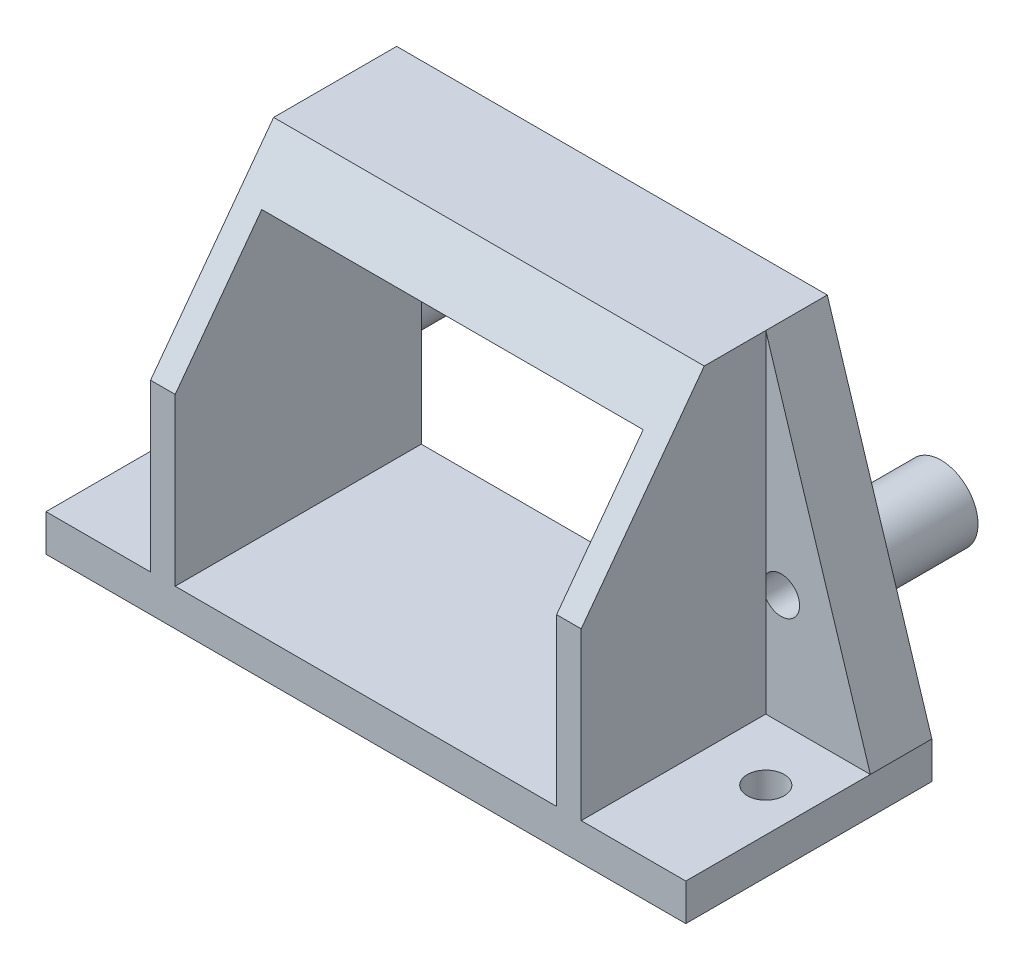
SolidWorks part; units mm, degrees
ref_plane "Front" through (0, 0, 0) normal (0, 0, 1) x (1, 0, 0)
ref_plane "Top" through (0, 0, 0) normal (0, 1, 0) x (1, 0, 0)
ref_plane "Right" through (0, 0, 0) normal (1, 0, 0) x (0, 0, -1)
sketch "草图1" plane through (0, 0, 0) normal (0, 0, 1) x (1, 0, 0)
  line L0 (-26, 0) -> (26, 0)
  line L1 (26, 0) -> (26, 3)
  line L2 (17.5, 30) -> (-17.5, 30)
  line L3 (-26, 3) -> (-26, 0)
  line L4 (-15.5, 3) -> (-15.5, 26)
  line L5 (-15.5, 26) -> (15.5, 26)
  line L6 (15.5, 26) -> (15.5, 3)
  line L7 (-15.5, 3) -> (15.5, 3)
  line L9 (17.5, 30) -> (26, 3)
  line L10 (-26, 3) -> (-17.5, 30)
extrude "凸台-拉伸1" add sketch "草图1" along normal blind 20
sketch "草图2" plane through (-15.5, 0, 0) normal (1, 0, 0) x (0, 0, -1)
  line L0 (-20, 16.5) -> (-10, 30)
  line L1 (-20, 3) -> (-20, 30) construction
  line L2 (-20, 30) -> (0, 30) construction
  line L3 (-10, 30) -> (-20, 30)
  line L4 (-20, 30) -> (-20, 16.5)
extrude "切除-拉伸1" cut sketch "草图2" against normal mid plane 92
sketch "草图3" plane through (0, 0, 20) normal (0, 0, 1) x (1, 0, 0)
  line L0 (17.5, 30) -> (17.5, 3)
  line L1 (17.5, 3) -> (26, 3)
  line L2 (26, 3) -> (21.75, 16.5) construction
  line L3 (26, 3) -> (17.5, 30)
  line L4 (-17.5, 30) -> (-26, 3)
  line L5 (-26, 3) -> (-17.5, 3)
  line L6 (-17.5, 3) -> (-17.5, 30)
extrude "切除-拉伸2" cut sketch "草图3" against normal blind 15
sketch "草图4" plane through (0, 0, 0) normal (0, -1, 0) x (1, 0, 0)
  circle A1 centre (-22.5, 10) radius 1.5
  circle A2 centre (22.5, 10) radius 1.5
extrude "切除-拉伸3" cut sketch "草图4" against normal blind 15
sketch "草图5" plane through (0, 0, 5) normal (0, 0, 1) x (1, 0, 0)
  circle A1 centre (-18.75, 12) radius 1.5
  circle A2 centre (18.75, 12) radius 1.5
extrude "切除-拉伸4" cut sketch "草图5" against normal blind 10
sketch "草图6" plane through (0, 0, 0) normal (0, 0, -1) x (-1, 0, 0)
  circle A0 centre (18.75, 12) radius 1.5
  circle A1 centre (18.75, 12) radius 3
  circle A2 centre (-18.75, 12) radius 1.5
  circle A3 centre (-18.75, 12) radius 3
extrude "凸台-拉伸2" add sketch "草图6" along normal blind 8
